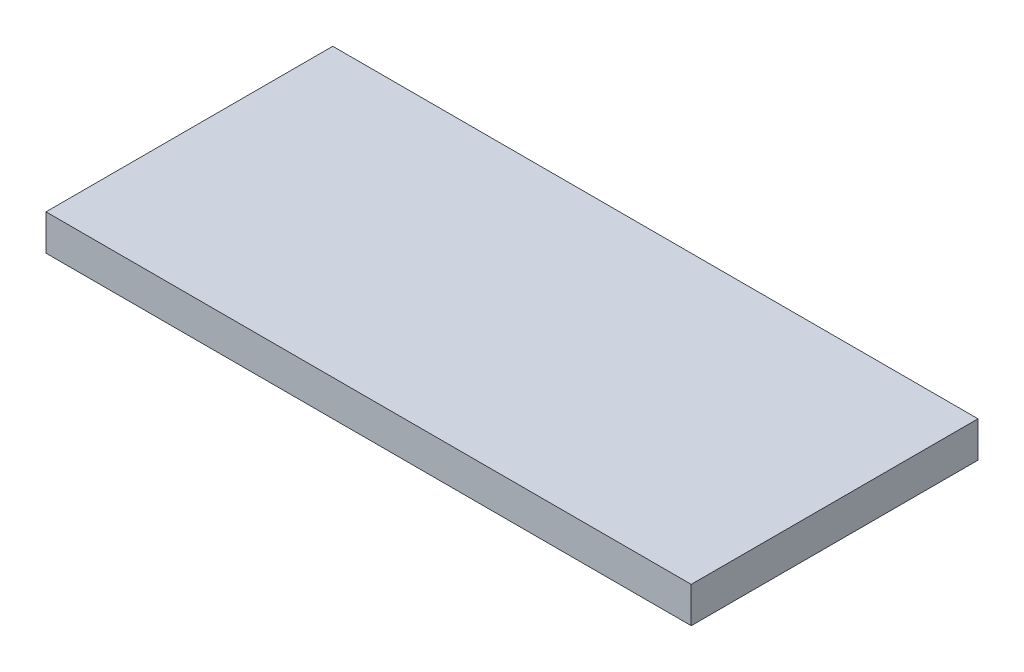
SolidWorks part; units mm, degrees
ref_plane "Front Plane" through (0, 0, 0) normal (0, 0, 1) x (1, 0, 0)
ref_plane "Top Plane" through (0, 0, 0) normal (0, 1, 0) x (1, 0, 0)
ref_plane "Right Plane" through (0, 0, 0) normal (1, 0, 0) x (0, 0, -1)
sketch "Sketch1" plane through (0, 0, 0) normal (0, 1, 0) x (1, 0, 0)
  line L1 (0, 0) -> (45.72, 0)
  line L2 (0, 0) -> (0, -20.32)
  line L3 (0, -20.32) -> (45.72, -20.32)
  line L4 (45.72, 0) -> (45.72, -20.32)
  dimension "D1" = 45.72
  dimension "D2" = 20.32
extrude "Boss-Extrude1" add sketch "Sketch1" along normal blind 2.54
